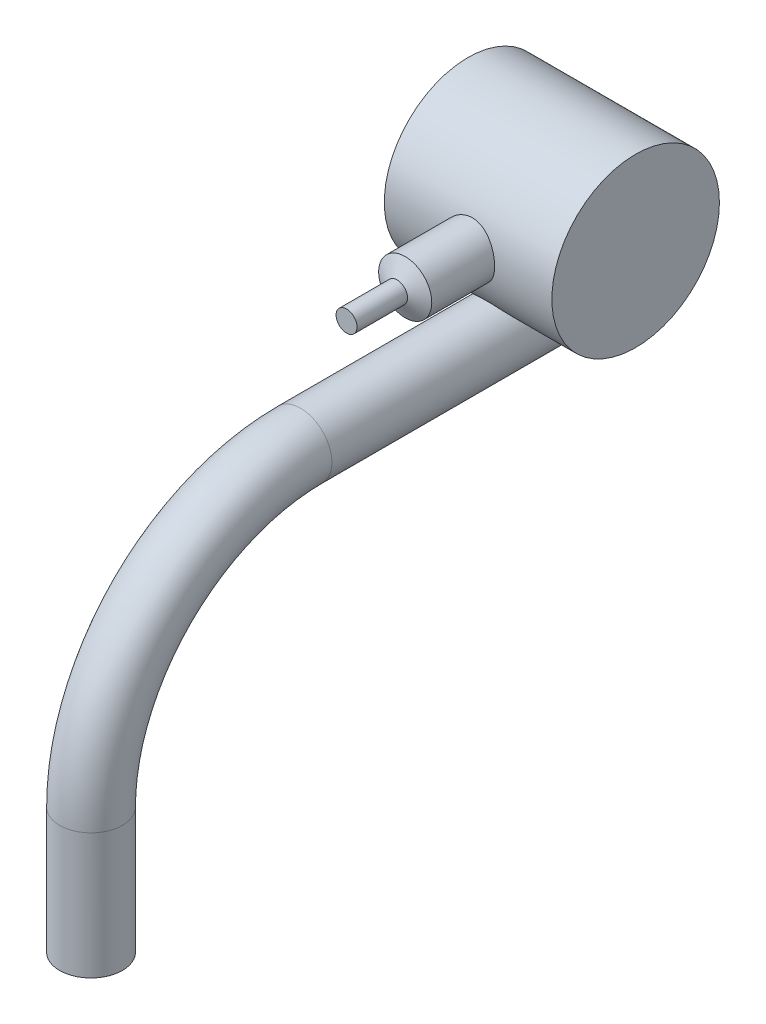
SolidWorks part; units mm, degrees
ref_plane "front" through (0, 0, 0) normal (0, 0, 1) x (1, 0, 0)
ref_plane "top" through (0, 0, 0) normal (0, 1, 0) x (1, 0, 0)
ref_plane "right" through (0, 0, 0) normal (1, 0, 0) x (0, 0, -1)
sketch "Sketch1" plane through (0, 0, 0) normal (1, 0, 0) x (0, 0, -1)
  circle A0 centre (0, 0) radius 12.7
  dimension "D1" = 25.4
extrude "Extrude1" add sketch "Sketch1" along normal mid plane 25.4
ref_plane "Plane1" through (0, 0, -12.7) normal (0, 0, 1) x (1, 0, 0)
sketch "Sketch2" plane through (0, 0, -12.7) normal (0, 0, 1) x (1, 0, 0)
  circle A0 centre (0, -12.7) radius 4.7625
  circle A1 centre (0, -12.7) radius 3.8735
  dimension "D1" = 9.525
  dimension "D2" = 12.7
  dimension "D3" = 0.889
sketch "Sketch3" plane through (0, 0, 0) normal (1, 0, 0) x (0, 0, -1)
  line L0 (12.7, -12.7) -> (-38.1, -12.7)
  line L1 (-69.85, -44.45) -> (-69.85, -63.5)
  arc A0 (-38.1, -12.7) -> (-69.85, -44.45) centre (-38.1, -44.45) ccw
  dimension "D3" = 31.75
  dimension "D1" = 50.8
  dimension "D2" = 69.85
sweep "Sweep1" add profiles "Sketch2" path "Sketch3"
sketch "Sketch4" plane through (0, 0, -12.7) normal (0, 0, 1) x (1, 0, 0)
  circle A0 centre (0, -12.7) radius 4.7625 construction
  circle A1 centre (0, -12.7) radius 4.7625
extrude "Extrude2" add sketch "Sketch4" along normal blind 0.889
sketch "Sketch5" plane through (0, 0, 0) normal (1, 0, 0) x (0, 0, -1)
  line L0 (-10.16, 0) -> (-31.115, 0)
  line L1 (-31.115, 0) -> (-31.115, 1.5875)
  line L2 (-31.115, 1.5875) -> (-23.4629, 1.5875)
  line L3 (-23.4629, 1.5875) -> (-22.225, 4.0259)
  line L4 (-22.225, 4.0259) -> (-10.16, 4.0259)
  line L5 (-10.16, 4.0259) -> (-10.16, 0)
  line L6 (-31.115, 0) -> (-51.3212, 0) construction
  dimension "D1" = 3.175
  dimension "D2" = 8.0518
  dimension "D3" = 22.225
  dimension "D4" = 8.89
  dimension "D5" = 10.16
revolve "Revolve1" add sketch "Sketch5" angle 360 about L6
